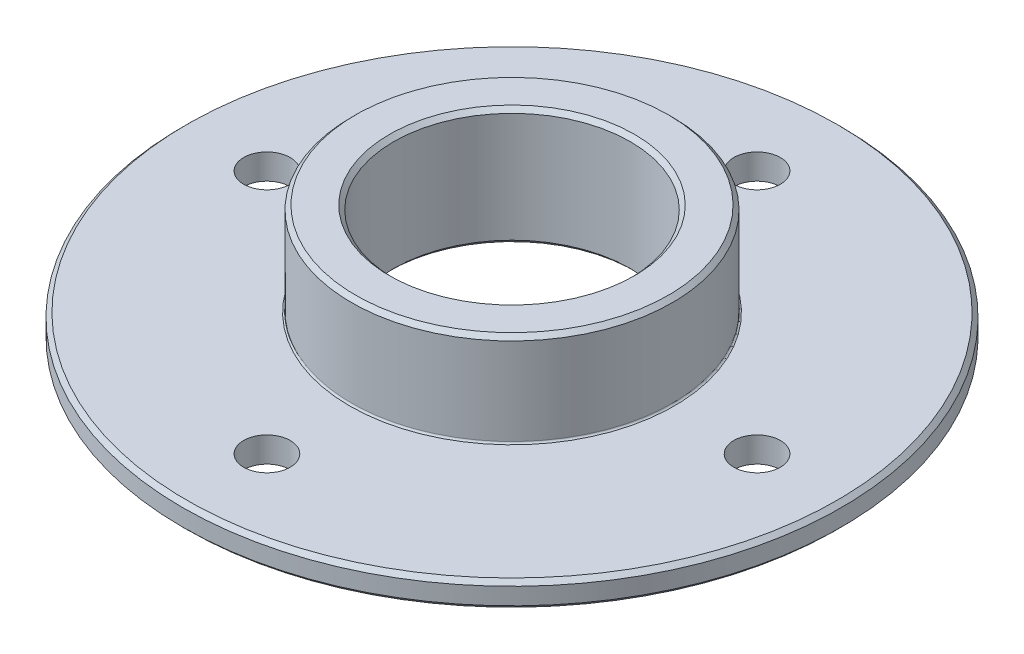
SolidWorks part; units mm, degrees
ref_plane "Front" through (0, 0, 0) normal (0, 0, 1) x (1, 0, 0)
ref_plane "Top" through (0, 0, 0) normal (0, 1, 0) x (1, 0, 0)
ref_plane "Right" through (0, 0, 0) normal (1, 0, 0) x (0, 0, -1)
sketch "Sketch1" plane through (0, 0, 0) normal (0, 0, 1) x (1, 0, 0)
  line L0 (0, 17.954) -> (0, -17.7415) construction
  line L2 (14, -3) -> (14, 8)
  line L4 (19, 11) -> (19, 0)
  line L5 (19, 0) -> (39, 0)
  line L6 (39, 0) -> (39, -3)
  line L7 (39, -3) -> (14, -3)
  line L9 (19, 11) -> (12, 11)
  line L10 (12, 11) -> (12, 8)
  line L11 (12, 8) -> (14, 8)
  point P3 (13, 8)
  point P12 (29, 0)
  dimension "D1" = 5
  dimension "D2" = 14
  dimension "D3" = 12
  dimension "D4" = 20
  dimension "D5" = 3
  dimension "D6" = 3
  dimension "D7" = 8
  dimension "D8" = 29
revolve "Revolve1" add sketch "Sketch1" angle 360 about L0
sketch "Sketch2" [suppressed] plane through (0, 0, 0) normal (0, 1, 0) x (1, 0, 0)
  circle A0 centre (0, 0) radius 11
extrude "Cut-Extrude1" [suppressed] cut sketch "Sketch2" against normal through all
ref_plane "Plane1" through (0, 17.954, 0) normal (-1, 0, 0) x (0, 0, 1)
hole_wizard "M5 Clearance Hole1" positions "Sketch5" profile "Sketch6" hole size "M5" standard "ISO" end condition through all
sketch "Sketch5" plane through (0, 0, 0) normal (0, 1, 0) x (1, 0, 0)
  circle A0 centre (0, 0) radius 29 construction
  point P0 (0, 29)
  point P7 (29, 0)
  point P9 (0, -29)
  point P11 (-29, 0)
  dimension "D1" = 58
sketch "Sketch6" plane through (0, 0, -29) normal (1, 0, 0) x (0, 0, 1)
  line L0 (0, 0) -> (0, 3)
  line L1 (0, 3) -> (2.75, 3)
  line L2 (2.75, 3) -> (2.75, 0)
  line L5 (2.75, 0) -> (0, 0)
  line L11 (0, -6.35) -> (0, 107.95) construction
  dimension "Thru Hole Dia." = 5.5
  dimension "Thru Hole Depth" = 3
fillet "Fillet1" radius 0.2 2 edges at (0, 0, 19) (0, 8, 14)
chamfer "Chamfer1" distance 0.5 angle 45 6 edges at (0, -3, 14) (0, 11, 19) (0, 11, 12) (0, 8, 12) (0, -3, 39) (0, 0, 39)
ref_plane "Plane2" through (0, 17.954, 0) normal (-1, 0, 0) x (0, 0, 1)
sketch "Sketch7" plane through (0, -3, 0) normal (0, -1, 0) x (1, 0, 0)
  circle A0 centre (0, 0) radius 14 construction
  circle A1 centre (0, 0) radius 14
extrude "Cut-Extrude2" cut sketch "Sketch7" against normal through all
chamfer "Chamfer2" distance 0.5 angle 45 1 edges at (0, 11, -14)
